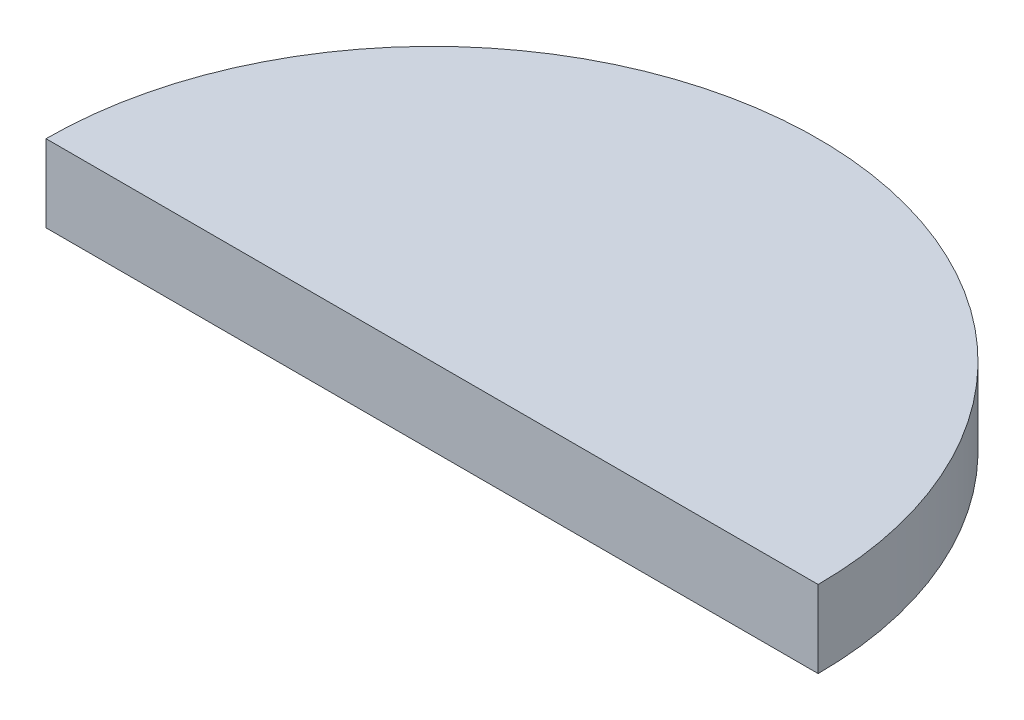
SolidWorks part; units mm, degrees
ref_plane "前视基准面" through (0, 0, 0) normal (0, 0, 1) x (1, 0, 0)
ref_plane "上视基准面" through (0, 0, 0) normal (0, 1, 0) x (1, 0, 0)
ref_plane "右视基准面" through (0, 0, 0) normal (1, 0, 0) x (0, 0, -1)
other "Configuration Table"
sketch "草图1" plane through (0, 0, 0) normal (0, 1, 0) x (1, 0, 0)
  line L0 (0, 0) -> (20, 0)
  arc A0 (20, 0) -> (0, 0) centre (10, 0) ccw
  dimension "D1" = 20
extrude "凸台-拉伸1" add sketch "草图1" along normal blind 2
